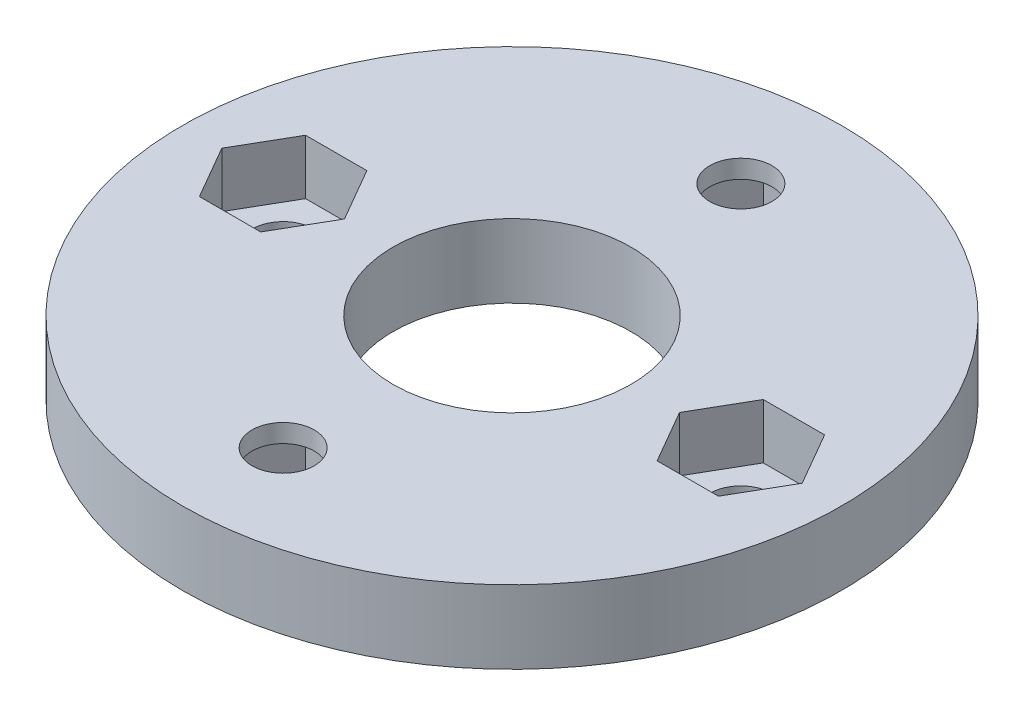
SolidWorks part; units mm, degrees
ref_plane "Спереди" through (0, 0, 0) normal (0, 0, 1) x (1, 0, 0)
ref_plane "Сверху" through (0, 0, 0) normal (0, 1, 0) x (1, 0, 0)
ref_plane "Справа" through (0, 0, 0) normal (1, 0, 0) x (0, 0, -1)
sketch "Эскиз1" plane through (0, 0, 0) normal (0, 1, 0) x (1, 0, 0)
  circle A0 centre (0, 0) radius 18
  circle A1 centre (0, 0) radius 6.5
  dimension "D1" = 13
  dimension "D2" = 36
extrude "тело" add sketch "Эскиз1" along normal blind 4
sketch "Эскиз2" plane through (0, 4, 0) normal (0, 1, 0) x (1, 0, 0)
  line L0 (-15.8486, 0) -> (-14.1743, -2.9)
  line L1 (15.8486, 0) -> (14.1743, 2.9)
  line L2 (14.1743, 2.9) -> (10.8257, 2.9)
  line L3 (10.8257, 2.9) -> (9.1514, 0)
  line L4 (9.1514, 0) -> (10.8257, -2.9)
  line L5 (10.8257, -2.9) -> (14.1743, -2.9)
  line L6 (14.1743, -2.9) -> (15.8486, 0)
  line L7 (-14.1743, -2.9) -> (-10.8257, -2.9)
  line L8 (-10.8257, -2.9) -> (-9.1514, 0)
  line L9 (-9.1514, 0) -> (-10.8257, 2.9)
  line L10 (-10.8257, 2.9) -> (-14.1743, 2.9)
  line L11 (-14.1743, 2.9) -> (-15.8486, 0)
  circle A0 centre (0, 0) radius 12.5 construction
  circle A1 centre (12.5, 0) radius 2.9 construction
  circle A2 centre (-12.5, 0) radius 2.9 construction
  point P21 (0, 0)
  dimension "D1" = 25
  dimension "D2" = 5.8
  dimension "D3" = 2
extrude "паз для гаек" cut sketch "Эскиз2" against normal blind 3
sketch "Эскиз3" plane through (0, 1, 0) normal (0, 1, 0) x (1, 0, 0)
  line L0 (9.1514, 0) -> (15.8486, 0) construction
  circle A0 centre (12.5, 0) radius 1.7
  dimension "D1" = 3.4
extrude "сквозное отверстие под гайкой" cut sketch "Эскиз3" against normal through all and the other way through all
pattern_circular "Круговой массив1" count 4 over 360 about axis through (0, 0, 0) along (0, 1, 0) of "сквозное отверстие под гайкой"
sketch "Эскиз4" [suppressed] plane through (0, 4, 0) normal (0, 1, 0) x (1, 0, 0)
  circle A0 centre (0, 0) radius 12.5 construction
  circle A1 centre (0, 12.5) radius 1.25
  dimension "D1" = 25
  dimension "D2" = 2.5
extrude "отверстие для шурупа" [suppressed] cut sketch "Эскиз4" against normal through all
sketch "Эскиз5" plane through (0, 0, 0) normal (0, -1, 0) x (1, 0, 0)
  line L1 (3.3486, 12.5) -> (1.6743, 15.4)
  line L2 (1.6743, 15.4) -> (-1.6743, 15.4)
  line L3 (-1.6743, 15.4) -> (-3.3486, 12.5)
  line L4 (-3.3486, 12.5) -> (-1.6743, 9.6)
  line L5 (-1.6743, 9.6) -> (1.6743, 9.6)
  line L6 (1.6743, 9.6) -> (3.3486, 12.5)
  line L12 (-3.3486, -12.5) -> (-1.6743, -15.4)
  line L13 (-1.6743, -15.4) -> (1.6743, -15.4)
  line L14 (1.6743, -15.4) -> (3.3486, -12.5)
  line L15 (3.3486, -12.5) -> (1.6743, -9.6)
  line L16 (1.6743, -9.6) -> (-1.6743, -9.6)
  line L17 (-1.6743, -9.6) -> (-3.3486, -12.5)
  circle A0 centre (0, 12.5) radius 2.9 construction
  circle A1 centre (0, -12.5) radius 2.9 construction
  point P19 (0, 0)
  point P21 (0, 0)
  dimension "D1" = 5.8
  dimension "D2" = 2
extrude "Углубления под гайки с другой стороны" cut sketch "Эскиз5" against normal blind 3
